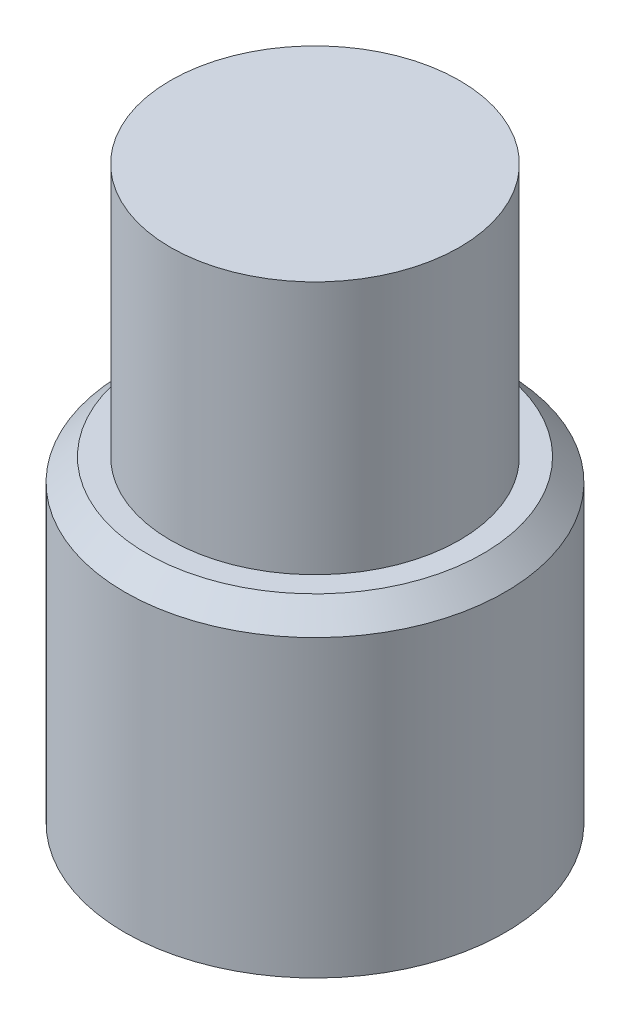
SolidWorks part; units mm, degrees
ref_plane "Front Plane" through (0, 0, 0) normal (0, 0, 1) x (1, 0, 0)
ref_plane "Top Plane" through (0, 0, 0) normal (0, 1, 0) x (1, 0, 0)
ref_plane "Right Plane" through (0, 0, 0) normal (1, 0, 0) x (0, 0, -1)
sketch "Sketch1" plane through (0, 0, 0) normal (0, 1, 0) x (1, 0, 0)
  circle A0 centre (0, 0) radius 2.28
extrude "Boss-Extrude1" add sketch "Sketch1" along normal blind 9
sketch "Sketch2" plane through (0, 0, 0) normal (0, -1, 0) x (-1, 0, 0)
  circle A0 centre (0, 0) radius 3
extrude "Boss-Extrude2" add sketch "Sketch2" against normal blind 5
chamfer "Chamfer1" distance 0.35 angle 45 1 edges at (0, 5, -3)
